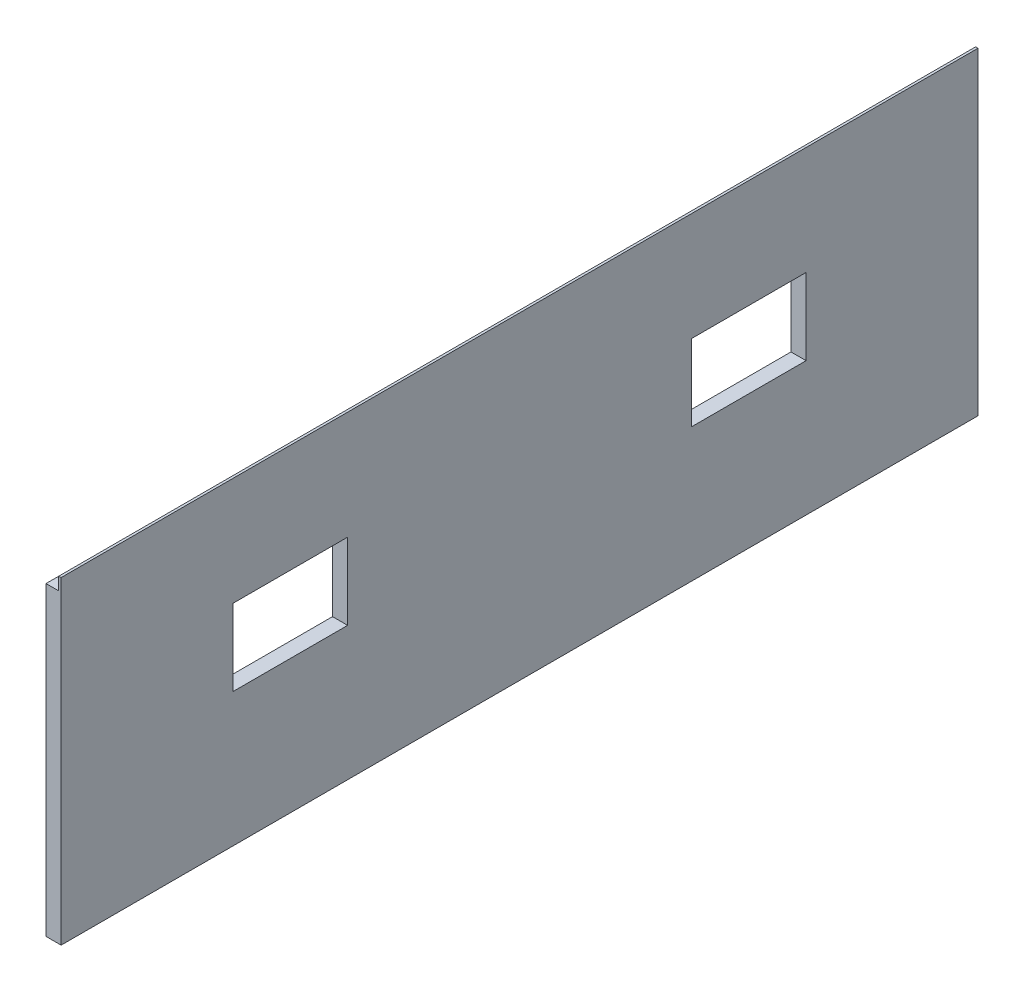
SolidWorks part; units mm, degrees
ref_plane "Front Plane" through (0, 0, 0) normal (0, 0, 1) x (1, 0, 0)
ref_plane "Top Plane" through (0, 0, 0) normal (0, 1, 0) x (1, 0, 0)
ref_plane "Right Plane" through (0, 0, 0) normal (1, 0, 0) x (0, 0, -1)
sketch "Sketch1" plane through (0, 0, 0) normal (1, 0, 0) x (0, 0, -1)
  line L0 (0, 0) -> (3657.6, 0)
  line L1 (3657.6, 0) -> (3657.6, 2438.4)
  line L2 (3657.6, 2438.4) -> (-3657.6, 2438.4)
  line L3 (-3657.6, 2438.4) -> (-3657.6, 0)
  line L4 (-3657.6, 0) -> (0, 0)
  line L5 (1828.8, 1778) -> (2006.6, 1778)
  line L10 (-3606.8, 2387.6) -> (-3276.6, 2387.6)
  line L11 (-3606.8, 2387.6) -> (-3606.8, 50.8)
  line L12 (-3606.8, 50.8) -> (-3276.6, 50.8)
  line L13 (3606.8, 2387.6) -> (3606.8, 50.8)
  line L14 (-1828.8, 1778) -> (-1651, 1778)
  line L17 (-2286, 1676.4) -> (-2286, 1066.8)
  line L19 (-1371.6, 1066.8) -> (-1371.6, 1676.4)
  line L25 (1828.8, 1676.4) -> (1371.6, 1676.4)
  line L26 (1371.6, 1676.4) -> (1371.6, 1066.8)
  line L27 (1371.6, 1066.8) -> (2286, 1066.8)
  line L28 (2286, 1066.8) -> (2286, 1676.4)
  line L29 (2286, 1676.4) -> (1828.8, 1676.4)
  line L33 (25.4, 50.8) -> (25.4, 2387.6)
  line L34 (-25.4, 50.8) -> (-25.4, 2387.6)
  line L35 (381, 50.8) -> (381, 2387.6)
  line L36 (431.8, 50.8) -> (431.8, 2387.6)
  line L37 (787.4, 50.8) -> (787.4, 2387.6)
  line L38 (838.2, 50.8) -> (838.2, 2387.6)
  line L39 (1193.8, 50.8) -> (1193.8, 2387.6)
  line L40 (1244.6, 50.8) -> (1244.6, 965.2)
  line L41 (1600.2, 50.8) -> (1600.2, 965.2)
  line L42 (1651, 50.8) -> (1651, 965.2)
  line L43 (2006.6, 50.8) -> (2006.6, 965.2)
  line L44 (2057.4, 50.8) -> (2057.4, 965.2)
  line L45 (2413, 50.8) -> (2413, 965.2)
  line L46 (2463.8, 50.8) -> (2463.8, 2387.6)
  line L47 (2819.4, 50.8) -> (2819.4, 2387.6)
  line L48 (2870.2, 50.8) -> (2870.2, 2387.6)
  line L49 (3225.8, 50.8) -> (3225.8, 2387.6)
  line L50 (3276.6, 50.8) -> (3276.6, 2387.6)
  line L51 (1600.2, 1778) -> (1600.2, 2387.6)
  line L52 (1651, 1778) -> (1651, 2387.6)
  line L53 (2006.6, 1778) -> (2006.6, 2387.6)
  line L54 (2057.4, 1778) -> (2057.4, 2387.6)
  line L56 (2006.6, 965.2) -> (1651, 965.2)
  line L57 (1651, 1778) -> (1828.8, 1778)
  line L59 (25.4, 2387.6) -> (381, 2387.6)
  line L60 (431.8, 2387.6) -> (787.4, 2387.6)
  line L61 (838.2, 2387.6) -> (1193.8, 2387.6)
  line L62 (1244.6, 2387.6) -> (1600.2, 2387.6)
  line L63 (1651, 2387.6) -> (2006.6, 2387.6)
  line L64 (2057.4, 2387.6) -> (2413, 2387.6)
  line L65 (2463.8, 2387.6) -> (2819.4, 2387.6)
  line L66 (2870.2, 2387.6) -> (3225.8, 2387.6)
  line L67 (3276.6, 2387.6) -> (3606.8, 2387.6)
  line L68 (3276.6, 50.8) -> (3606.8, 50.8)
  line L69 (2870.2, 50.8) -> (3225.8, 50.8)
  line L70 (2463.8, 50.8) -> (2819.4, 50.8)
  line L71 (2057.4, 50.8) -> (2413, 50.8)
  line L72 (1651, 50.8) -> (2006.6, 50.8)
  line L73 (1244.6, 50.8) -> (1600.2, 50.8)
  line L74 (838.2, 50.8) -> (1193.8, 50.8)
  line L75 (431.8, 50.8) -> (787.4, 50.8)
  line L76 (25.4, 50.8) -> (381, 50.8)
  line L79 (1600.2, 1778) -> (1244.6, 1778)
  line L80 (1600.2, 965.2) -> (1244.6, 965.2)
  line L81 (1244.6, 1778) -> (1244.6, 2387.6)
  line L84 (2057.4, 1778) -> (2413, 1778)
  line L85 (2057.4, 965.2) -> (2413, 965.2)
  line L86 (2413, 1778) -> (2413, 2387.6)
  line L87 (-431.8, 50.8) -> (-431.8, 2387.6)
  line L88 (-381, 50.8) -> (-381, 2387.6)
  line L89 (-838.2, 50.8) -> (-838.2, 2387.6)
  line L90 (-787.4, 50.8) -> (-787.4, 2387.6)
  line L91 (-1244.6, 50.8) -> (-1244.6, 965.2)
  line L92 (-1193.8, 50.8) -> (-1193.8, 2387.6)
  line L93 (-1651, 50.8) -> (-1651, 965.2)
  line L94 (-1600.2, 50.8) -> (-1600.2, 965.2)
  line L95 (-2057.4, 50.8) -> (-2057.4, 965.2)
  line L96 (-2006.6, 50.8) -> (-2006.6, 965.2)
  line L97 (-2463.8, 50.8) -> (-2463.8, 2387.6)
  line L98 (-2413, 50.8) -> (-2413, 965.2)
  line L99 (-2870.2, 50.8) -> (-2870.2, 2387.6)
  line L100 (-2819.4, 50.8) -> (-2819.4, 2387.6)
  line L101 (-3276.6, 50.8) -> (-3276.6, 2387.6)
  line L102 (-3225.8, 50.8) -> (-3225.8, 2387.6)
  line L103 (-3225.8, 2387.6) -> (-2870.2, 2387.6)
  line L104 (-2819.4, 2387.6) -> (-2463.8, 2387.6)
  line L105 (-2413, 2387.6) -> (-2057.4, 2387.6)
  line L106 (-2006.6, 2387.6) -> (-1651, 2387.6)
  line L107 (-1600.2, 2387.6) -> (-1244.6, 2387.6)
  line L108 (-1193.8, 2387.6) -> (-838.2, 2387.6)
  line L109 (-787.4, 2387.6) -> (-431.8, 2387.6)
  line L110 (-381, 2387.6) -> (-25.4, 2387.6)
  line L111 (-381, 50.8) -> (-25.4, 50.8)
  line L112 (-787.4, 50.8) -> (-431.8, 50.8)
  line L113 (-1193.8, 50.8) -> (-838.2, 50.8)
  line L114 (-1600.2, 50.8) -> (-1244.6, 50.8)
  line L115 (-2006.6, 50.8) -> (-1651, 50.8)
  line L116 (-2413, 50.8) -> (-2057.4, 50.8)
  line L117 (-2819.4, 50.8) -> (-2463.8, 50.8)
  line L118 (-3225.8, 50.8) -> (-2870.2, 50.8)
  line L123 (-2057.4, 1778) -> (-2057.4, 2387.6)
  line L124 (-2006.6, 1778) -> (-2006.6, 2387.6)
  line L125 (-1651, 1778) -> (-1651, 2387.6)
  line L126 (-1600.2, 1778) -> (-1600.2, 2387.6)
  line L130 (-1651, 965.2) -> (-2006.6, 965.2)
  line L133 (-2006.6, 1778) -> (-1828.8, 1778)
  line L135 (-2057.4, 1778) -> (-2413, 1778)
  line L136 (-2057.4, 965.2) -> (-2413, 965.2)
  line L137 (-2286, 1676.4) -> (-1371.6, 1676.4)
  line L138 (-2286, 1066.8) -> (-1371.6, 1066.8)
  line L139 (-2413, 1778) -> (-2413, 2387.6)
  line L140 (-1600.2, 1778) -> (-1244.6, 1778)
  line L141 (-1600.2, 965.2) -> (-1244.6, 965.2)
  line L142 (-1244.6, 1778) -> (-1244.6, 2387.6)
  dimension "D1" = 2
  dimension "D2" = 9
  dimension "D3" = 9
extrude "Boss-Extrude1" add sketch "Sketch1" along normal blind 101.6
sketch "Sketch2" plane through (101.6, 0, 0) normal (1, 0, 0) x (0, 0, -1)
  line L1 (-3657.6, 2438.4) -> (3657.6, 2438.4)
  line L2 (-3657.6, 2438.4) -> (-3657.6, 0)
  line L3 (-3657.6, 0) -> (3657.6, 0)
  line L4 (3657.6, 2438.4) -> (3657.6, 0)
  line L5 (1371.6, 1676.4) -> (2286, 1676.4)
  line L6 (1371.6, 1676.4) -> (1371.6, 1066.8)
  line L7 (1371.6, 1066.8) -> (2286, 1066.8)
  line L8 (2286, 1676.4) -> (2286, 1066.8)
  line L9 (-2286, 1676.4) -> (-1371.6, 1676.4)
  line L10 (-2286, 1676.4) -> (-2286, 1066.8)
  line L11 (-2286, 1066.8) -> (-1371.6, 1066.8)
  line L12 (-1371.6, 1676.4) -> (-1371.6, 1066.8)
extrude "Boss-Extrude2" add sketch "Sketch2" along normal blind 19.05
sketch "Sketch3" plane through (0, 2438.4, 0) normal (0, 1, 0) x (1, 0, 0)
  line L0 (120.65, -3657.6) -> (0, -3657.6) construction
  line L1 (120.65, 3657.6) -> (101.6, 3657.6)
  line L2 (120.65, 3657.6) -> (120.65, -3657.6)
  line L3 (120.65, -3657.6) -> (101.6, -3657.6)
  line L4 (101.6, 3657.6) -> (101.6, -3657.6)
extrude "Boss-Extrude3" add sketch "Sketch3" along normal blind 101.6
